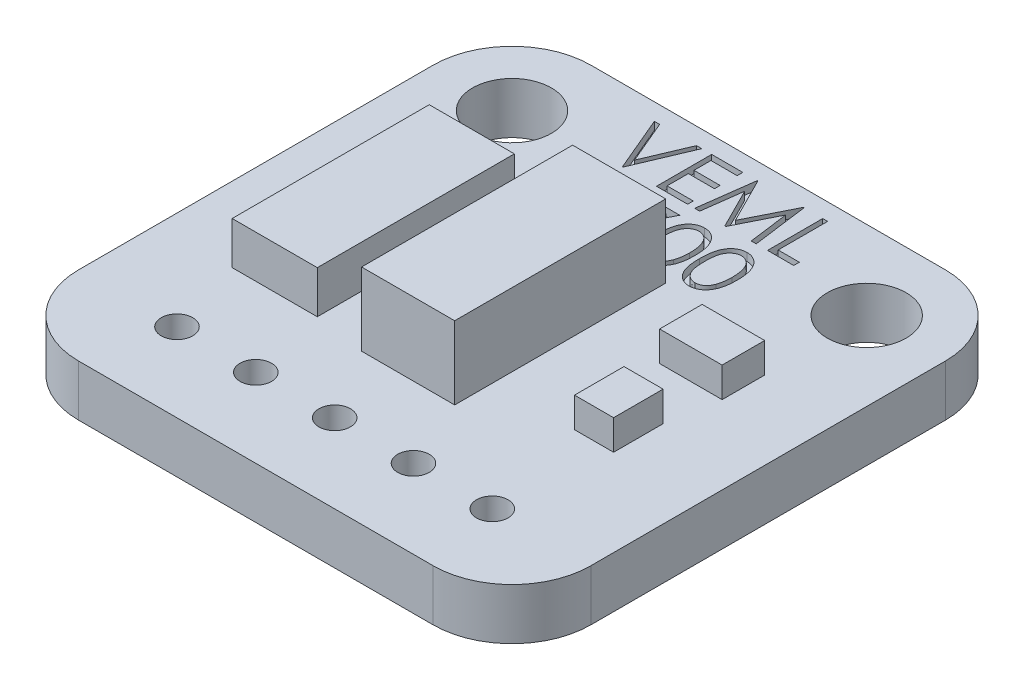
SolidWorks part; units mm, degrees
ref_plane "Front Plane" through (0, 0, 0) normal (0, 0, 1) x (1, 0, 0)
ref_plane "Top Plane" through (0, 0, 0) normal (0, 1, 0) x (1, 0, 0)
ref_plane "Right Plane" through (0, 0, 0) normal (1, 0, 0) x (0, 0, -1)
sketch "Sketch1" plane through (0, 0, 0) normal (0, 1, 0) x (1, 0, 0)
  line L1 (-8.255, -8.255) -> (8.255, -8.255)
  line L2 (-8.255, -8.255) -> (-8.255, 8.255)
  line L3 (-8.255, 8.255) -> (8.255, 8.255)
  line L4 (8.255, -8.255) -> (8.255, 8.255)
  line L5 (-8.255, -8.255) -> (8.255, 8.255) construction
  line L6 (-8.255, 8.255) -> (8.255, -8.255) construction
  point P0 (0, 0)
  dimension "D1" = 16.51
  dimension "D2" = 16.51
extrude "Boss-Extrude1" add sketch "Sketch1" along normal blind 1.651
sketch "Sketch2" plane through (0, 1.651, 0) normal (0, 1, 0) x (1, 0, 0)
  line L0 (0, 0) -> (0, 8.255) construction
  line L1 (8.255, 8.255) -> (-8.255, 8.255) construction
  circle A0 centre (-5.715, 5.715) radius 1.27
  circle A1 centre (5.715, 5.715) radius 1.27
  dimension "D1" = 2.54
  dimension "D2" = 11.43
  dimension "D3" = 2.54
extrude "Cut-Extrude1" cut sketch "Sketch2" against normal through all
fillet "Fillet1" radius 2.54 4 edges at (-8.255, 0.8255, -8.255) (8.255, 0.8255, -8.255) (8.255, 0.8255, 8.255) (-8.255, 0.8255, 8.255)
sketch "Sketch3" plane through (0, 1.651, 0) normal (0, 1, 0) x (1, 0, 0)
  line L0 (5.715, 8.255) -> (-5.715, 8.255) construction
  line L1 (-1.4252, 3.3782) -> (1.5748, 3.3782)
  line L2 (-1.4252, 3.3782) -> (-1.4252, -3.4218)
  line L3 (-1.4252, -3.4218) -> (1.5748, -3.4218)
  line L4 (1.5748, 3.3782) -> (1.5748, -3.4218)
  line L5 (8.255, -5.715) -> (8.255, 5.715) construction
  line L6 (-1.4252, 3.3782) -> (1.5748, -3.4218) construction
  line L7 (1.5748, 3.3782) -> (-1.4252, -3.4218) construction
  line L9 (-1.4252, -3.4218) -> (1.5748, -3.4218) construction
  line L10 (-1.4252, -3.4218) -> (-1.4252, 3.3782) construction
  line L11 (-1.4252, 3.3782) -> (1.5748, 3.3782) construction
  line L12 (1.5748, -3.4218) -> (1.5748, 3.3782) construction
  line L13 (-1.4252, -3.4218) -> (1.5748, 3.3782) construction
  line L14 (-1.4252, 3.3782) -> (1.5748, -3.4218) construction
  point P8 (0.0748, -0.0218)
  dimension "D1" = 3
  dimension "D2" = 6.8
  dimension "D3" = 4.8768
  dimension "D4" = 6.6802
extrude "Boss-Extrude2" add sketch "Sketch3" along normal blind 2.35 separate body
sketch "Sketch4" plane through (0, 1.651, 0) normal (0, 1, 0) x (1, 0, 0)
  line L0 (0, -8.255) -> (0, -5.715) construction
  line L1 (-5.715, -8.255) -> (5.715, -8.255) construction
  circle A0 centre (0, -5.715) radius 0.508
  dimension "D1" = 1.016
  dimension "D2" = 2.54
extrude "Cut-Extrude2" cut sketch "Sketch4" against normal through all
pattern_linear "LPattern1" count 3 spacing 2.54 along (1, 0, 0) count 3 spacing 2.54 along (-1, 0, 0) of "Cut-Extrude2"
sketch "Sketch5" plane through (0, 1.651, 0) normal (0, 1, 0) x (1, 0, 0)
  line L0 (-3.7136, 5.9318) -> (3.7136, 5.9318) construction
  line L1 (-3.7136, 3.7203) -> (3.7136, 3.7203) construction
  line L2 (0, 0) -> (0, 5.9318) construction
  text T0 "VEML" font "Century Gothic" height 1.778
  text T1 "7700" font "Century Gothic" height 1.778
  point P8 (0, 3.7203)
  dimension "D1" = 7.4273
extrude "Cut-Extrude3" cut sketch "Sketch5" against normal blind 0.254
sketch "Sketch6" plane through (0, 1.651, 0) normal (0, 1, 0) x (1, 0, 0)
  line L0 (-3.0988, 0) -> (0, 0) construction
  line L1 (-5.842, 3.175) -> (-3.0988, 3.175)
  line L2 (-5.842, 3.175) -> (-5.842, -3.175)
  line L3 (-5.842, -3.175) -> (-3.0988, -3.175)
  line L4 (-3.0988, 3.175) -> (-3.0988, -3.175)
  line L5 (3.7211, 2.4061) -> (5.7356, 2.4061)
  line L6 (3.7211, 2.4061) -> (3.7211, 1.0352)
  line L7 (3.7211, 1.0352) -> (5.7356, 1.0352)
  line L8 (5.7356, 2.4061) -> (5.7356, 1.0352)
  line L9 (4.1968, -0.5875) -> (5.4558, -0.5875)
  line L10 (4.1968, -0.5875) -> (4.1968, -2.1823)
  line L11 (4.1968, -2.1823) -> (5.4558, -2.1823)
  line L12 (5.4558, -0.5875) -> (5.4558, -2.1823)
  line L13 (-8.255, 5.715) -> (-8.255, -5.715) construction
  dimension "D1" = 6.35
  dimension "D2" = 2.7432
  dimension "D3" = 2.413
extrude "Boss-Extrude3" add sketch "Sketch6" along normal offset from surface (1.3716 mm away) 3.0226 separate body up to face at (5.08, 0, 6.223)
sketch "Sketch7" plane through (0, 3.0226, 0) normal (0, 1, 0) x (1, 0, 0)
  line L1 (3.1336, 2.7978) -> (6.491, 2.7978)
  line L2 (3.1336, 2.7978) -> (3.1336, -2.63)
  line L3 (3.1336, -2.63) -> (6.491, -2.63)
  line L4 (6.491, 2.7978) -> (6.491, -2.63)
extrude "Cut-Extrude4" cut sketch "Sketch7" against normal offset from surface (0.4064 mm away) 2.6162 up to face at (5.08, 0, 6.223)
sketch "Sketch8" plane through (0, 1.651, 0) normal (0, 1, 0) x (1, 0, 0)
  line L1 (-1.2743, -2.8704) -> (1.2743, -2.8704)
  line L2 (-1.2743, -2.8704) -> (-1.2743, 2.8704)
  line L3 (-1.2743, 2.8704) -> (1.2743, 2.8704)
  line L4 (1.2743, -2.8704) -> (1.2743, 2.8704)
  line L5 (-1.2743, -2.8704) -> (1.2743, 2.8704) construction
  line L6 (-1.2743, 2.8704) -> (1.2743, -2.8704) construction
  point P0 (0, 0)
extrude "Boss-Extrude4" add sketch "Sketch8" along normal blind 0.762 separate body
sketch "Sketch9" plane through (0, 2.413, 0) normal (0, 1, 0) x (1, 0, 0)
  line L0 (0, 0) -> (0.6393, 0) construction
  line L1 (0.2583, -0.381) -> (1.0203, -0.381)
  line L2 (0.2583, -0.381) -> (0.2583, 0.381)
  line L3 (0.2583, 0.381) -> (1.0203, 0.381)
  line L4 (1.0203, -0.381) -> (1.0203, 0.381)
  line L5 (0.2583, -0.381) -> (1.0203, 0.381) construction
  line L6 (0.2583, 0.381) -> (1.0203, -0.381) construction
  line L7 (1.2743, -2.8704) -> (1.2743, 2.8704) construction
  point P0 (0.6393, 0)
  dimension "D1" = 0.762
  dimension "D2" = 0.254
extrude "Boss-Extrude5" add sketch "Sketch9" along normal blind 0.508 separate body
